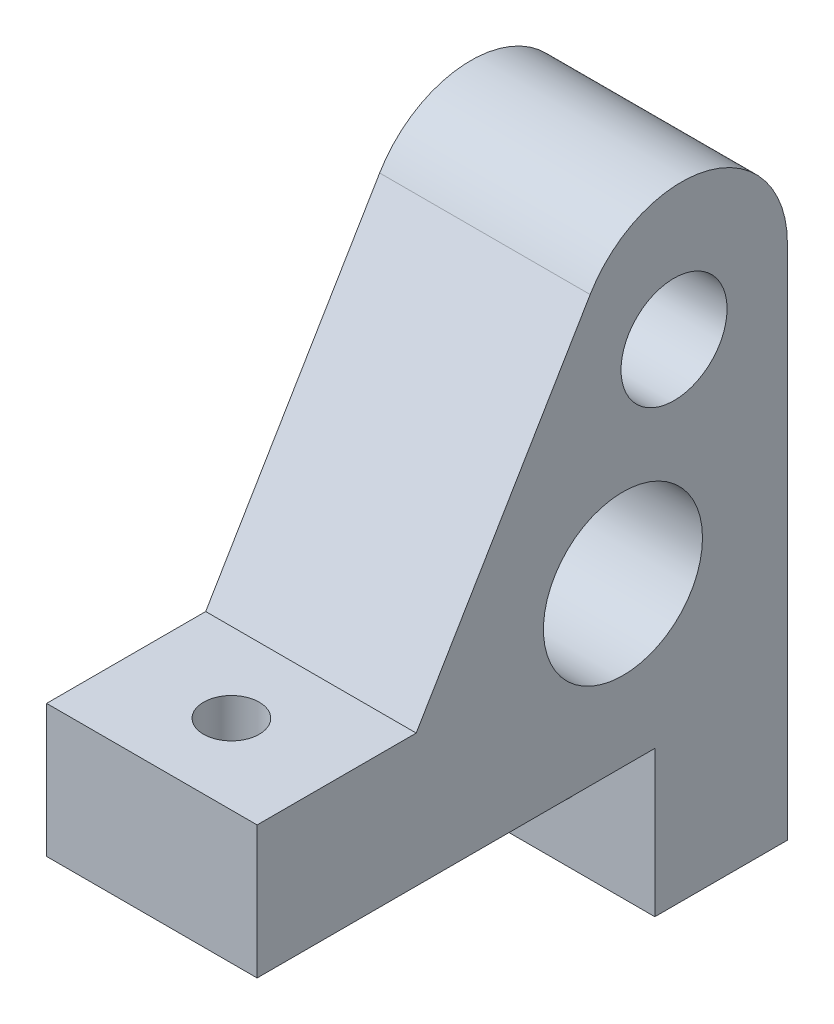
SolidWorks part; units mm, degrees
material "6063-T6"
ref_plane "Plano frontal" through (0, 0, 0) normal (0, 0, 1) x (1, 0, 0)
ref_plane "Plano superior" through (0, 0, 0) normal (0, 1, 0) x (1, 0, 0)
ref_plane "Plano direito" through (0, 0, 0) normal (1, 0, 0) x (0, 0, -1)
sketch "Esboço1" plane through (0, 0, 0) normal (1, 0, 0) x (0, 0, -1)
  line L0 (-40, 0) -> (-10, 0)
  line L1 (-14.8777, 32.0863) -> (-28, 10)
  line L2 (0, 28) -> (0, 0)
  line L3 (-28, 10) -> (-40, 10)
  line L4 (-40, 10) -> (-40, 0)
  line L5 (-10, 0) -> (-10, -11)
  line L6 (-10, -11) -> (0, -11)
  line L7 (0, -11) -> (0, 0)
  line L8 (0, 28) -> (0, 36) construction
  line L9 (0, 36) -> (-28, 36) construction
  line L10 (-28, 36) -> (-28, 10) construction
  arc A0 (-14.8777, 32.0863) -> (0, 28) centre (-8, 28) cw
  dimension "D5" = 8
  dimension "D1" = 40
  dimension "D2" = 10
  dimension "D3" = 36
  dimension "D4" = 12
  dimension "D6" = 30
  dimension "D7" = 11
extrude "Ressalto-extrusão1" add sketch "Esboço1" along normal mid plane 15.88
hole_wizard "Broca de rosquear para tarraxa de M5x0.81" positions "Esboço2" profile "Esboço3" hole size "M5x0.8" standard "Ansi Metric"
sketch "Esboço2" plane through (33.065, 10, -11.4602) normal (0, 1, 0) x (1, 0, 0)
  line L0 (41, -45.4602) -> (25.12, -45.4602) construction
  line L3 (-41.005, -45.4602) -> (-25.125, -45.4602) construction
  point P9 (33.06, -45.4602)
  point P20 (-33.065, -45.4602)
sketch "Esboço3" plane through (66.125, 10, 34) normal (1, 0, 0) x (0, 0, 1)
  line L0 (0, 0) -> (0, 21.2618)
  line L1 (0, 21.2618) -> (2.1, 20)
  line L2 (2.1, 20) -> (2.1, 0)
  line L3 (2.1, 0) -> (0, 0)
  line L4 (0, 21.2618) -> (-2.1, 20) construction
  line L5 (0, -6.35) -> (0, 107.95) construction
  dimension "Hole Dia." = 4.2
  dimension "Hole Depth" = 20
  dimension "Drill Angle" = 118
hole_wizard "Broca de rosquear para tarraxa de M5x0.82" positions "Esboço4" profile "Esboço5" hole size "M5x0.8" standard "Ansi Metric"
sketch "Esboço4" plane through (-33.06, 10, -11.4602) normal (0, 1, 0) x (1, 0, 0)
  line L0 (41, -45.4602) -> (25.12, -45.4602) construction
  line L3 (-41.005, -45.4602) -> (-25.125, -45.4602) construction
  point P9 (33.06, -45.4602)
  point P20 (-33.065, -45.4602)
sketch "Esboço5" plane through (0, 10, 34) normal (1, 0, 0) x (0, 0, 1)
  line L0 (0, 0) -> (0, 21.2618)
  line L1 (0, 21.2618) -> (2.1, 20)
  line L2 (2.1, 20) -> (2.1, 0)
  line L3 (2.1, 0) -> (0, 0)
  line L4 (0, 21.2618) -> (-2.1, 20) construction
  line L5 (0, -6.35) -> (0, 107.95) construction
  dimension "Hole Dia." = 4.2
  dimension "Hole Depth" = 20
  dimension "Drill Angle" = 118
hole_wizard "Broca de rosquear para tarraxa de M5x0.83" positions "Esboço6" profile "Esboço7" hole size "M5x0.8" standard "Ansi Metric"
sketch "Esboço6" plane through (33.065, -48.7517, 0) normal (0, 0, -1) x (-1, 0, 0)
  line L0 (-33.06, 37.7517) -> (-33.06, 43.7517) construction
  line L3 (33.065, 37.7517) -> (33.065, 43.7517) construction
  point P1 (-33.06, 43.7517)
  point P7 (33.065, 43.7517)
sketch "Esboço7" plane through (66.125, -5, 0) normal (1, 0, 0) x (0, 1, 0)
  line L0 (0, 0) -> (0, 21.2618)
  line L1 (0, 21.2618) -> (2.1, 20)
  line L2 (2.1, 20) -> (2.1, 0)
  line L3 (2.1, 0) -> (0, 0)
  line L4 (0, 21.2618) -> (-2.1, 20) construction
  line L5 (0, -6.35) -> (0, 107.95) construction
  dimension "Hole Dia." = 4.2
  dimension "Hole Depth" = 20
  dimension "Drill Angle" = 118
hole_wizard "Broca de rosquear para tarraxa de M5x0.84" positions "Esboço8" profile "Esboço9" hole size "M5x0.8" standard "Ansi Metric"
sketch "Esboço8" plane through (-33.06, -48.7517, 0) normal (0, 0, -1) x (-1, 0, 0)
  line L0 (-33.06, 37.7517) -> (-33.06, 43.7517) construction
  line L3 (33.065, 37.7517) -> (33.065, 43.7517) construction
  point P1 (-33.06, 43.7517)
  point P7 (33.065, 43.7517)
sketch "Esboço9" plane through (0, -5, 0) normal (1, 0, 0) x (0, 1, 0)
  line L0 (0, 0) -> (0, 21.2618)
  line L1 (0, 21.2618) -> (2.1, 20)
  line L2 (2.1, 20) -> (2.1, 0)
  line L3 (2.1, 0) -> (0, 0)
  line L4 (0, 21.2618) -> (-2.1, 20) construction
  line L5 (0, -6.35) -> (0, 107.95) construction
  dimension "Hole Dia." = 4.2
  dimension "Hole Depth" = 20
  dimension "Drill Angle" = 118
sketch "Esboço10" plane through (7.94, 0, 0) normal (1, 0, 0) x (0, 0, -1)
  line L0 (-14.8777, 32.0863) -> (-28, 10) construction
  line L1 (-12.405, 11.962) -> (-23.0697, 18.2983) construction
  line L2 (-12.405, 11.962) -> (0, 11.962) construction
  line L3 (0, -11) -> (0, 28) construction
  line L4 (0, 25.9935) -> (-8.5511, 25.9935) construction
  line L5 (-8.5511, 25.9935) -> (-15.9026, 30.3613) construction
  line L6 (-8.5511, 25.9935) -> (-10.8159, 17.7477) construction
  line L7 (-12.405, 11.962) -> (-15.6905, 0) construction
  line L8 (-40, 0) -> (-10, 0) construction
  circle A0 centre (-12.405, 11.962) radius 6
  circle A1 centre (-8.5511, 25.9935) radius 4
  dimension "D1" = 12
  dimension "D2" = 8
extrude "Corte-extrusão1" cut sketch "Esboço10" against normal through all
